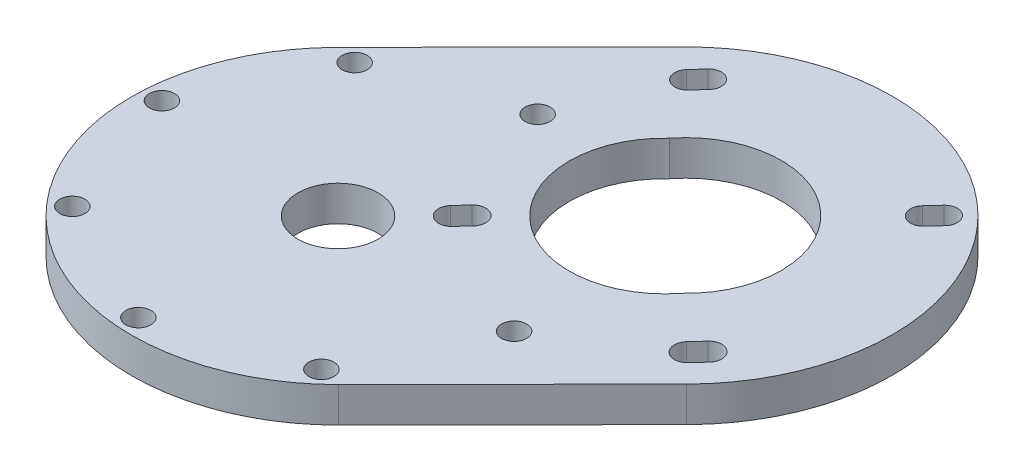
SolidWorks part; units mm, degrees
ref_plane "Front Plane" through (0, 0, 0) normal (0, 0, 1) x (1, 0, 0)
ref_plane "Top Plane" through (0, 0, 0) normal (0, 1, 0) x (1, 0, 0)
ref_plane "Right Plane" through (0, 0, 0) normal (1, 0, 0) x (0, 0, -1)
sketch "Sketch2" plane through (0, 0, 0) normal (0, 1, 0) x (1, 0, 0)
  line L7 (37.7819, 49.5452) -> (39.8275, 51.7804)
  line L8 (41.476, 46.1643) -> (43.5217, 48.3995)
  line L10 (84.7843, 49.5429) -> (86.83, 51.7781)
  line L11 (88.4736, 46.1665) -> (90.5193, 48.4017)
  line L12 (39.629, 0.8547) -> (39.6311, 0.857) construction
  line L13 (37.7433, 2.5805) -> (39.7889, 4.8157)
  line L14 (41.5146, -0.8711) -> (43.5603, 1.3641)
  line L16 (84.7355, 2.5877) -> (86.7811, 4.8229)
  line L17 (88.5224, -0.8782) -> (90.5681, 1.357)
  line L21 (-0.8356, 18.5793) -> (33.7483, 53.3302)
  line L22 (57.4857, -39.4616) -> (92.0695, -4.7108)
  arc A3 (41.3972, 2.622) -> (41.3168, 2.6989) centre (39.629, 0.8547) ccw
  arc A4 (47.9145, 35.9789) -> (75.8576, 10.4053) centre (60.8632, 22.0745) ccw
  arc A10 (39.9868, 1.2457) -> (40.0042, 1.2299) centre (41.6746, 3.0899) ccw
  arc A11 (75.8576, 10.4053) -> (47.9145, 35.9789) centre (62.9089, 24.3097) ccw
  arc A12 (37.7819, 49.5452) -> (41.476, 46.1643) centre (39.629, 47.8547) ccw
  arc A13 (43.5217, 48.3995) -> (39.8275, 51.7804) centre (41.6746, 50.0899) ccw
  arc A14 (84.7843, 49.5429) -> (88.4736, 46.1665) centre (86.629, 47.8547) ccw
  arc A15 (90.5193, 48.4017) -> (86.83, 51.7781) centre (88.6746, 50.0899) ccw
  arc A16 (37.7433, 2.5805) -> (41.5146, -0.8711) centre (39.629, 0.8547) ccw
  arc A17 (43.5603, 1.3641) -> (39.7889, 4.8157) centre (41.6746, 3.0899) ccw
  arc A18 (84.7355, 2.5877) -> (88.5224, -0.8782) centre (86.629, 0.8547) ccw
  arc A19 (90.5681, 1.357) -> (86.7811, 4.8229) centre (88.6746, 3.0899) ccw
  circle A23 centre (28.325, -10.4412) radius 8
  arc A24 (-0.8356, 18.5793) -> (57.4857, -39.4616) centre (28.325, -10.4412) ccw
  arc A25 (92.0695, -4.7108) -> (33.7483, 53.3302) centre (62.9089, 24.3097) ccw
  circle A27 centre (-48.7874, 22.0745) radius 2.5
  point P1 (45.617, 6.9343)
  point P9 (52.1531, 13.4658)
  point P19 (60.8632, 22.0745)
  point P30 (40.6518, 48.9723)
  point P35 (87.6518, 48.9723)
  point P40 (40.6518, 1.9723)
  point P45 (87.6518, 1.9723)
extrude "Boss-Extrude1" add sketch "Sketch2" along normal blind 7 contours L22 A25 L21 A24 A11 A4 A13 L8 A12 L7 A15 L11 A14 L10 A17 L14 A16 L13 A19 L17 A18 L16 A23
sketch "Sketch6" plane through (0, 7, 0) normal (0, 1, 0) x (1, 0, 0)
  circle A1 centre (3.5171, 17.6803) radius 2.5
extrude "Cut-Extrude2" cut sketch "Sketch6" against normal blind 10
pattern_circular "CirPattern1" count 8 over 360 about axis through (28.325, 0, 10.4412) along (0, 1, 0) of "Cut-Extrude2"
